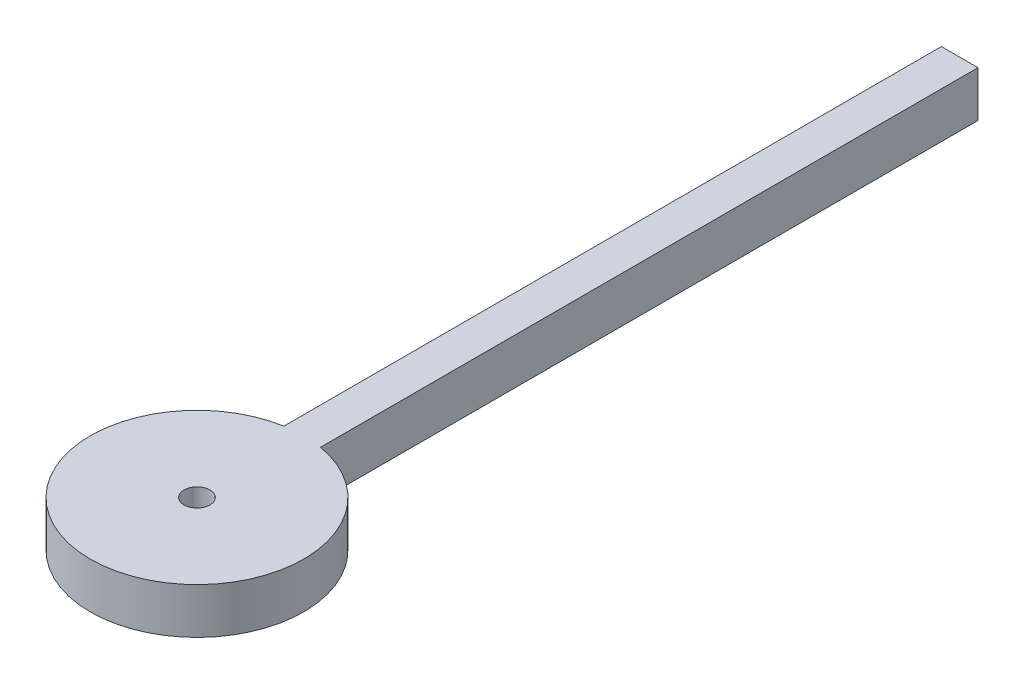
SolidWorks part; units mm, degrees
ref_plane "Front Plane" through (0, 0, 0) normal (0, 0, 1) x (1, 0, 0)
ref_plane "Top Plane" through (0, 0, 0) normal (0, 1, 0) x (1, 0, 0)
ref_plane "Right Plane" through (0, 0, 0) normal (1, 0, 0) x (0, 0, -1)
sketch "Sketch2" plane through (0, 0, 0) normal (0, 1, 0) x (1, 0, 0)
  line L1 (0.12, 0.6896) -> (0.12, 5)
  line L2 (-0.12, 0.6896) -> (-0.12, 5)
  line L4 (-0.12, 5) -> (0.12, 5)
  arc A2 (0.12, 0.6896) -> (-0.12, 0.6896) centre (0, 0) cw
  point P3 (0, 0)
extrude "Boss-Extrude1" add sketch "Sketch2" along normal blind 0.3
sketch "Sketch3" plane through (0, 0.3, 0) normal (0, 1, 0) x (1, 0, 0)
  circle A0 centre (0, 0) radius 0.085
extrude "Cut-Extrude1" cut sketch "Sketch3" against normal blind 0.3
